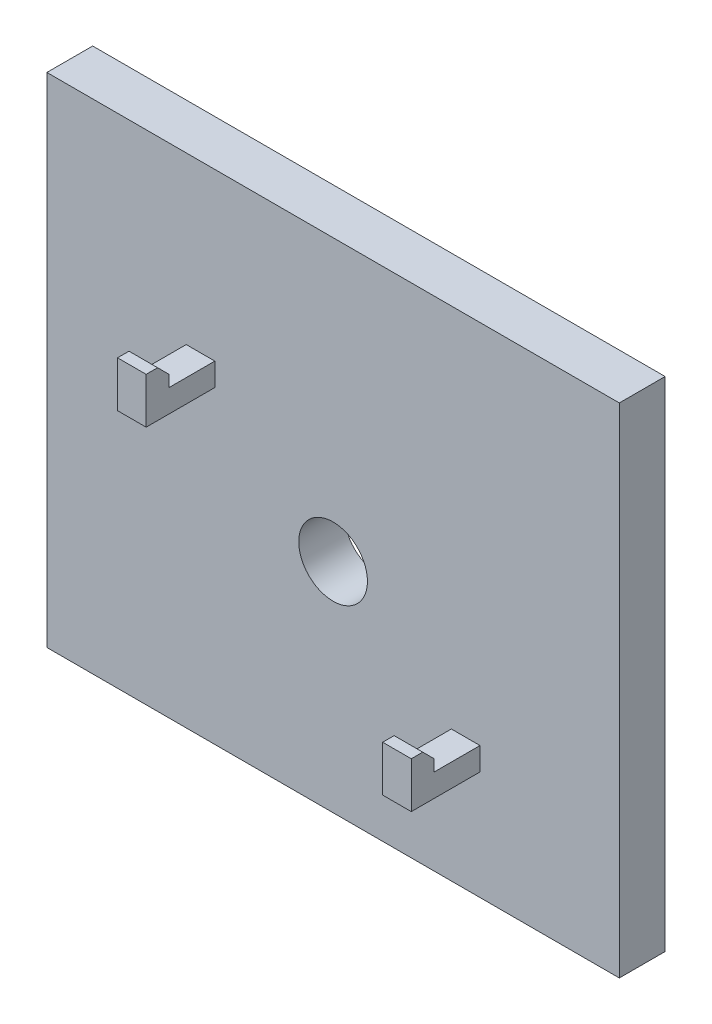
SolidWorks part; units mm, degrees
ref_plane "Alzado" through (0, 0, 0) normal (0, 0, 1) x (1, 0, 0)
ref_plane "Planta" through (0, 0, 0) normal (0, 1, 0) x (1, 0, 0)
ref_plane "Vista lateral" through (0, 0, 0) normal (1, 0, 0) x (0, 0, -1)
sketch "Croquis1" plane through (0, 0, 0) normal (0, 0, 1) x (1, 0, 0)
  line L1 (-25, -21.75) -> (25, -21.75)
  line L2 (-25, -21.75) -> (-25, 21.75)
  line L3 (-25, 21.75) -> (25, 21.75)
  line L4 (25, -21.75) -> (25, 21.75)
  line L5 (-25, -21.75) -> (25, 21.75) construction
  line L6 (-25, 21.75) -> (25, -21.75) construction
  point P0 (0, 0)
  dimension "D1" = 50
  dimension "D2" = 43.5
extrude "Saliente-Extruir1" add sketch "Croquis1" along normal blind 4
sketch "Croquis2" plane through (0, 0, 4) normal (0, 0, 1) x (1, 0, 0)
  line L0 (-25, -21.75) -> (25, -21.75) construction
  circle A0 centre (0, -2.75) radius 3
  point P4 (0, -21.75)
  dimension "D1" = 6
  dimension "D2" = 19
extrude "Cortar-Extruir1" cut sketch "Croquis2" against normal blind 4
sketch "Croquis3" plane through (0, 0, 4) normal (0, 0, 1) x (1, 0, 0)
  line L0 (-25, -21.75) -> (25, -21.75) construction
  line L1 (-12.83, -12.25) -> (-10.33, -12.25) construction
  line L2 (-12.83, -12.25) -> (-12.83, -10.25) construction
  line L3 (-12.83, -10.25) -> (-10.33, -10.25) construction
  line L4 (-10.33, -12.25) -> (-10.33, -10.25) construction
  line L5 (-12.83, -12.25) -> (-10.33, -10.25) construction
  line L6 (-12.83, -10.25) -> (-10.33, -12.25) construction
  line L7 (0, -21.75) -> (0, -16.2134) construction
  line L8 (-12.83, 5.25) -> (-10.33, 5.25)
  line L9 (-12.83, 5.25) -> (-12.83, 7.25)
  line L10 (-12.83, 7.25) -> (-10.33, 7.25)
  line L11 (-10.33, 5.25) -> (-10.33, 7.25)
  line L12 (-12.83, 5.25) -> (-10.33, 7.25) construction
  line L13 (-12.83, 7.25) -> (-10.33, 5.25) construction
  line L14 (12.83, 7.25) -> (10.33, 5.25) construction
  line L15 (12.83, 5.25) -> (10.33, 7.25) construction
  line L16 (12.83, -10.25) -> (10.33, -12.25) construction
  line L17 (12.83, -12.25) -> (10.33, -10.25) construction
  line L18 (10.33, 5.25) -> (10.33, 7.25) construction
  line L19 (12.83, 7.25) -> (10.33, 7.25) construction
  line L20 (12.83, 5.25) -> (12.83, 7.25) construction
  line L21 (12.83, 5.25) -> (10.33, 5.25) construction
  line L22 (10.33, -12.25) -> (10.33, -10.25)
  line L23 (12.83, -10.25) -> (10.33, -10.25)
  line L24 (12.83, -12.25) -> (12.83, -10.25)
  line L25 (12.83, -12.25) -> (10.33, -12.25)
  point P0 (-11.58, -11.25)
  point P7 (0, -21.75)
  point P8 (-11.58, 6.25)
  point P23 (11.58, 6.25)
  point P24 (11.58, -11.25)
  dimension "D1" = 10.5
  dimension "D2" = 11.58
  dimension "D3" = 2.5
  dimension "D4" = 2
  dimension "D5" = 2.5
  dimension "D6" = 2
  dimension "D7" = 28
extrude "Saliente-Extruir2" add sketch "Croquis3" along normal blind 6
sketch "Croquis4" plane through (0, 7.25, 0) normal (0, 1, 0) x (1, 0, 0)
  line L0 (-10.33, -10) -> (-10.33, -4) construction
  line L1 (-12.83, -10) -> (-10.33, -10)
  line L2 (-12.83, -10) -> (-12.83, -8)
  line L3 (-12.83, -8) -> (-10.33, -8)
  line L4 (-10.33, -10) -> (-10.33, -8)
  dimension "D1" = 2
extrude "Saliente-Extruir3" add sketch "Croquis4" along normal blind 2
sketch "Croquis5" plane through (0, -10.25, 0) normal (0, 1, 0) x (1, 0, 0)
  line L0 (12.83, -10) -> (12.83, -4) construction
  line L1 (10.33, -10) -> (12.83, -10)
  line L2 (10.33, -10) -> (10.33, -8)
  line L3 (10.33, -8) -> (12.83, -8)
  line L4 (12.83, -10) -> (12.83, -8)
  dimension "D1" = 2
extrude "Saliente-Extruir4" add sketch "Croquis5" along normal blind 2
chamfer "Chaflán1" distance 1 angle 45 2 edges at (-11.58, 9.25, 8) (11.58, -8.25, 8)
